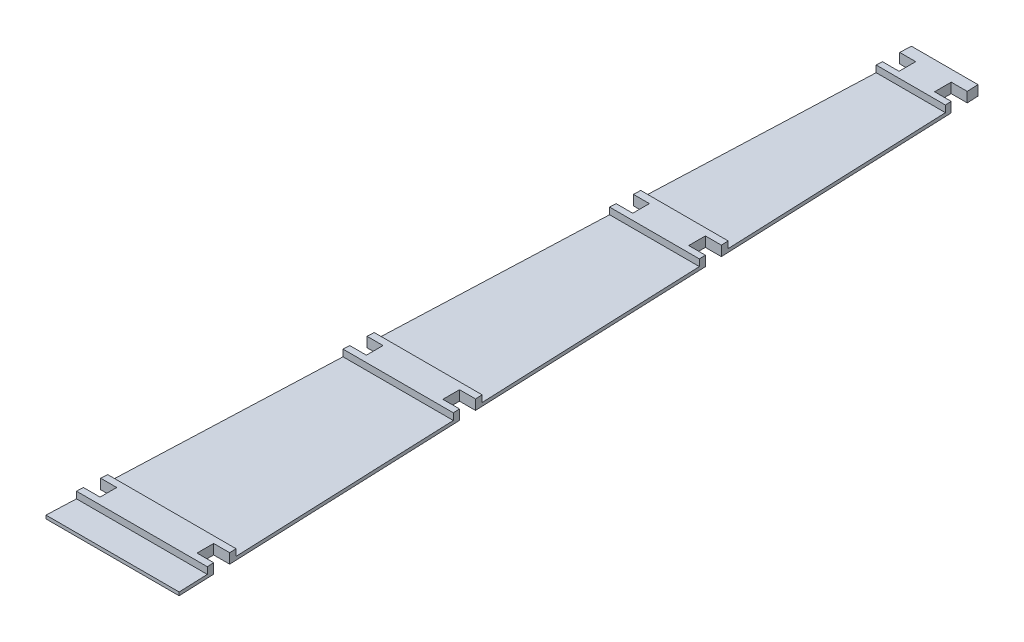
SolidWorks part; units mm, degrees
ref_plane "Front Plane" through (0, 0, 0) normal (0, 0, 1) x (1, 0, 0)
ref_plane "Top Plane" through (0, 0, 0) normal (0, 1, 0) x (1, 0, 0)
ref_plane "Right Plane" through (0, 0, 0) normal (1, 0, 0) x (0, 0, -1)
sketch "Sketch2" plane through (0, 0, 0) normal (0, 1, 0) x (1, 0, 0)
  line L0 (0, 0) -> (5, 125)
  line L1 (0, 0) -> (20, 0)
  line L5 (5, 125) -> (15, 125)
  line L7 (10, 125) -> (10, 0) construction
  line L8 (0.2161, 5.4015) -> (2.7192, 5.4015)
  line L10 (0.3162, 7.9046) -> (2.7192, 7.9046)
  line L11 (2.7192, 5.4015) -> (2.7192, 7.9046)
  line L36 (0.2161, 5.4015) -> (0.9755, 24.3863) construction
  line L37 (1.7548, 43.8707) -> (4.258, 43.8707)
  line L38 (4.258, 43.8707) -> (4.258, 46.3739)
  line L39 (1.855, 46.3739) -> (4.258, 46.3739)
  line L40 (3.2936, 82.34) -> (5.7967, 82.34)
  line L41 (5.7967, 82.34) -> (5.7967, 84.8431)
  line L42 (3.3937, 84.8431) -> (5.7967, 84.8431)
  line L43 (4.8324, 120.8092) -> (7.3355, 120.8092)
  line L44 (7.3355, 120.8092) -> (7.3355, 123.3123)
  line L45 (4.9325, 123.3123) -> (7.3355, 123.3123)
  line L46 (19.7839, 5.4015) -> (19.0245, 24.3863) construction
  line L47 (15.0675, 123.3123) -> (12.6645, 123.3123)
  line L48 (12.6645, 120.8092) -> (12.6645, 123.3123)
  line L49 (15.1676, 120.8092) -> (12.6645, 120.8092)
  line L50 (16.6063, 84.8431) -> (14.2033, 84.8431)
  line L51 (14.2033, 82.34) -> (14.2033, 84.8431)
  line L52 (16.7064, 82.34) -> (14.2033, 82.34)
  line L53 (18.145, 46.3739) -> (15.742, 46.3739)
  line L54 (15.742, 43.8707) -> (15.742, 46.3739)
  line L55 (18.2452, 43.8707) -> (15.742, 43.8707)
  line L56 (17.2808, 5.4015) -> (17.2808, 7.9046)
  line L57 (19.6838, 7.9046) -> (17.2808, 7.9046)
  line L58 (19.7839, 5.4015) -> (17.2808, 5.4015)
  line L61 (20, 0) -> (15, 125)
  dimension "D2" = 87.709
extrude "Boss-Extrude1" add sketch "Sketch2" along normal blind 0.5
sketch "Sketch3" plane through (0, 0.5, 0) normal (0, 1, 0) x (1, 0, 0)
  line L0 (0.1761, 4.4015) -> (19.8239, 4.4015)
  line L1 (0, 0) -> (0.2161, 5.4015) construction
  line L2 (20, 0) -> (19.7839, 5.4015) construction
  line L3 (19.6438, 8.9046) -> (0.3562, 8.9046)
  line L4 (19.6838, 7.9046) -> (18.2452, 43.8707) construction
  line L5 (0.3162, 7.9046) -> (1.7548, 43.8707) construction
  line L6 (0.3162, 7.9046) -> (2.7192, 7.9046) construction
  line L7 (0.2161, 5.4015) -> (2.7192, 5.4015) construction
  line L8 (19.6438, 47.4046) -> (0.3562, 47.4046)
  line L9 (0.1761, 42.9015) -> (19.8239, 42.9015)
  line L10 (19.6438, 85.9046) -> (0.3562, 85.9046)
  line L11 (0.1761, 81.4015) -> (19.8239, 81.4015)
  line L12 (19.6438, 124.4046) -> (0.3562, 124.4046)
  line L13 (0.1761, 119.9015) -> (19.8239, 119.9015)
  line L50 (0, 0) -> (20, 0)
  line L51 (20, 0) -> (19.7839, 5.4015)
  line L52 (19.7839, 5.4015) -> (17.2808, 5.4015)
  line L53 (17.2808, 5.4015) -> (17.2808, 7.9046)
  line L54 (17.2808, 7.9046) -> (19.6838, 7.9046)
  line L55 (19.6838, 7.9046) -> (18.2452, 43.8707)
  line L56 (18.2452, 43.8707) -> (15.742, 43.8707)
  line L57 (15.742, 43.8707) -> (15.742, 46.3739)
  line L58 (15.742, 46.3739) -> (18.145, 46.3739)
  line L59 (18.145, 46.3739) -> (16.7064, 82.34)
  line L60 (16.7064, 82.34) -> (14.2033, 82.34)
  line L61 (14.2033, 82.34) -> (14.2033, 84.8431)
  line L62 (14.2033, 84.8431) -> (16.6063, 84.8431)
  line L63 (16.6063, 84.8431) -> (15.1676, 120.8092)
  line L64 (15.1676, 120.8092) -> (12.6645, 120.8092)
  line L65 (12.6645, 120.8092) -> (12.6645, 123.3123)
  line L66 (12.6645, 123.3123) -> (15.0675, 123.3123)
  line L67 (15.0675, 123.3123) -> (15, 125)
  line L68 (15, 125) -> (5, 125)
  line L69 (5, 125) -> (4.9325, 123.3123)
  line L70 (4.9325, 123.3123) -> (7.3355, 123.3123)
  line L71 (7.3355, 123.3123) -> (7.3355, 120.8092)
  line L72 (7.3355, 120.8092) -> (4.8324, 120.8092)
  line L73 (4.8324, 120.8092) -> (3.3937, 84.8431)
  line L74 (3.3937, 84.8431) -> (5.7967, 84.8431)
  line L75 (5.7967, 84.8431) -> (5.7967, 82.34)
  line L76 (5.7967, 82.34) -> (3.2936, 82.34)
  line L77 (3.2936, 82.34) -> (1.855, 46.3739)
  line L78 (1.855, 46.3739) -> (4.258, 46.3739)
  line L79 (4.258, 46.3739) -> (4.258, 43.8707)
  line L80 (4.258, 43.8707) -> (1.7548, 43.8707)
  line L81 (1.7548, 43.8707) -> (0.3162, 7.9046)
  line L82 (0.3162, 7.9046) -> (2.7192, 7.9046)
  line L83 (2.7192, 7.9046) -> (2.7192, 5.4015)
  line L84 (2.7192, 5.4015) -> (0.2161, 5.4015)
  line L85 (0.2161, 5.4015) -> (0, 0)
  line L86 (0, 0) -> (20, 0)
  line L87 (20, 0) -> (19.7839, 5.4015)
  line L88 (19.7839, 5.4015) -> (17.2808, 5.4015)
  line L89 (17.2808, 5.4015) -> (17.2808, 7.9046)
  line L90 (17.2808, 7.9046) -> (19.6838, 7.9046)
  line L91 (19.6838, 7.9046) -> (18.2452, 43.8707)
  line L92 (18.2452, 43.8707) -> (15.742, 43.8707)
  line L93 (15.742, 43.8707) -> (15.742, 46.3739)
  line L94 (15.742, 46.3739) -> (18.145, 46.3739)
  line L95 (18.145, 46.3739) -> (16.7064, 82.34)
  line L96 (16.7064, 82.34) -> (14.2033, 82.34)
  line L97 (14.2033, 82.34) -> (14.2033, 84.8431)
  line L98 (14.2033, 84.8431) -> (16.6063, 84.8431)
  line L99 (16.6063, 84.8431) -> (15.1676, 120.8092)
  line L100 (15.1676, 120.8092) -> (12.6645, 120.8092)
  line L101 (12.6645, 120.8092) -> (12.6645, 123.3123)
  line L102 (12.6645, 123.3123) -> (15.0675, 123.3123)
  line L103 (15.0675, 123.3123) -> (15, 125)
  line L104 (15, 125) -> (5, 125)
  line L105 (5, 125) -> (4.9325, 123.3123)
  line L106 (4.9325, 123.3123) -> (7.3355, 123.3123)
  line L107 (7.3355, 123.3123) -> (7.3355, 120.8092)
  line L108 (7.3355, 120.8092) -> (4.8324, 120.8092)
  line L109 (4.8324, 120.8092) -> (3.3937, 84.8431)
  line L110 (3.3937, 84.8431) -> (5.7967, 84.8431)
  line L111 (5.7967, 84.8431) -> (5.7967, 82.34)
  line L112 (5.7967, 82.34) -> (3.2936, 82.34)
  line L113 (3.2936, 82.34) -> (1.855, 46.3739)
  line L114 (1.855, 46.3739) -> (4.258, 46.3739)
  line L115 (4.258, 46.3739) -> (4.258, 43.8707)
  line L116 (4.258, 43.8707) -> (1.7548, 43.8707)
  line L117 (1.7548, 43.8707) -> (0.3162, 7.9046)
  line L118 (0.3162, 7.9046) -> (2.7192, 7.9046)
  line L119 (2.7192, 7.9046) -> (2.7192, 5.4015)
  line L120 (2.7192, 5.4015) -> (0.2161, 5.4015)
  line L121 (0.2161, 5.4015) -> (0, 0)
  point P16 (1.4676, 5.4015)
  line M40 (20, 0) -> (19.7839, 5.4015)
  line M41 (19.7839, 5.4015) -> (17.2808, 5.4015)
  line M42 (17.2808, 5.4015) -> (17.2808, 7.9046)
  line M43 (17.2808, 7.9046) -> (19.6838, 7.9046)
  line M44 (19.6838, 7.9046) -> (18.2452, 43.8707)
  line M45 (18.2452, 43.8707) -> (15.742, 43.8707)
  line M46 (15.742, 43.8707) -> (15.742, 46.3739)
  line M47 (15.742, 46.3739) -> (18.145, 46.3739)
  line M48 (18.145, 46.3739) -> (16.7064, 82.34)
  line M49 (16.7064, 82.34) -> (14.2033, 82.34)
  line M50 (14.2033, 82.34) -> (14.2033, 84.8431)
  line M51 (14.2033, 84.8431) -> (16.6063, 84.8431)
  line M52 (16.6063, 84.8431) -> (15.1676, 120.8092)
  line M53 (15.1676, 120.8092) -> (12.6645, 120.8092)
  line M54 (12.6645, 120.8092) -> (12.6645, 123.3123)
  line M55 (12.6645, 123.3123) -> (15.0675, 123.3123)
  line M56 (15.0675, 123.3123) -> (15, 125)
  line M57 (15, 125) -> (5, 125)
  line M58 (5, 125) -> (4.9325, 123.3123)
  line M59 (4.9325, 123.3123) -> (7.3355, 123.3123)
  line M60 (7.3355, 123.3123) -> (7.3355, 120.8092)
  line M61 (7.3355, 120.8092) -> (4.8324, 120.8092)
  line M62 (4.8324, 120.8092) -> (3.3937, 84.8431)
  line M63 (3.3937, 84.8431) -> (5.7967, 84.8431)
  line M64 (5.7967, 84.8431) -> (5.7967, 82.34)
  line M65 (5.7967, 82.34) -> (3.2936, 82.34)
  line M66 (3.2936, 82.34) -> (1.855, 46.3739)
  line M67 (1.855, 46.3739) -> (4.258, 46.3739)
  line M68 (4.258, 46.3739) -> (4.258, 43.8707)
  line M69 (4.258, 43.8707) -> (1.7548, 43.8707)
  line M70 (1.7548, 43.8707) -> (0.3162, 7.9046)
  line M71 (0.3162, 7.9046) -> (2.7192, 7.9046)
  line M72 (2.7192, 7.9046) -> (2.7192, 5.4015)
  line M73 (2.7192, 5.4015) -> (0.2161, 5.4015)
  line M74 (0.2161, 5.4015) -> (0, 0)
  dimension "D1" = 1
  dimension "D2" = 1
  dimension "D4" = 0
  dimension "D3" = 4
extrude "Boss-Extrude2" add sketch "Sketch3" along normal blind 1 contours L3 L0 M44 M70 M71 M72 M73 M74 M40 M41 M42 M43 | L9 L8 M70 M44 M45 M46 M47 M48 M66 M67 M68 M69 | L11 L10 M66 M48 M49 M50 M51 M52 M62 M63 M64 M65 | L13 L12 M62 M52 M53 M54 M55 M56 M58 M59 M60 M61 | L12 M56 M57 M58
